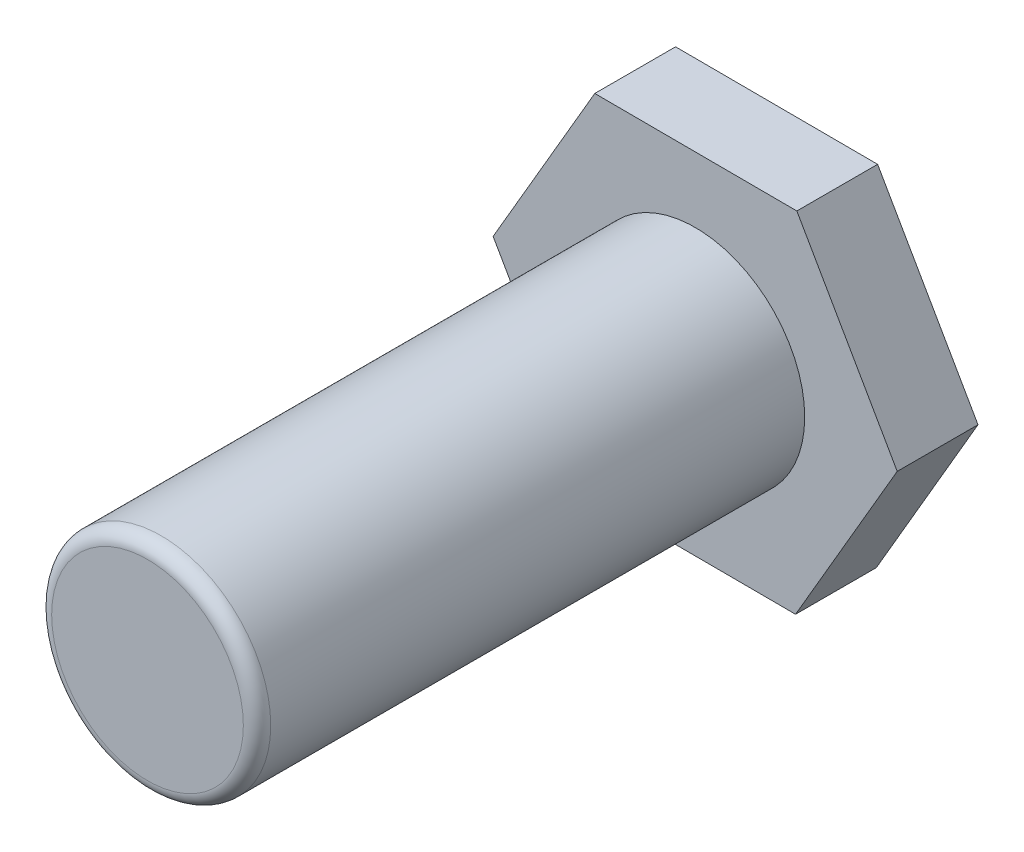
SolidWorks part; units mm, degrees
material "1.4021 (X20Cr13)"
ref_plane "Ön Düzlem" through (0, 0, 0) normal (0, 0, 1) x (1, 0, 0)
ref_plane "Üst Düzlem" through (0, 0, 0) normal (0, 1, 0) x (1, 0, 0)
ref_plane "Sağ Düzlem" through (0, 0, 0) normal (1, 0, 0) x (0, 0, -1)
sketch "Çizim2" plane through (0, 0, 0) normal (0, 0, 1) x (1, 0, 0)
  line L1 (3.7128, 6.3763) -> (-3.6656, 6.4036)
  line L2 (-3.6656, 6.4036) -> (-7.3785, 0.0273)
  line L3 (-7.3785, 0.0273) -> (-3.7128, -6.3763)
  line L4 (-3.7128, -6.3763) -> (3.6656, -6.4036)
  line L5 (3.6656, -6.4036) -> (7.3785, -0.0273)
  line L6 (7.3785, -0.0273) -> (3.7128, 6.3763)
  circle A0 centre (0, 0) radius 6.39 construction
  dimension "D1" = 12.78
extrude "Yükseklik-Ekstrüzyon1" add sketch "Çizim2" along normal blind 2.95
sketch "Çizim3" plane through (0, 0, 2.95) normal (0, 0, 1) x (1, 0, 0)
  circle A0 centre (0, 0) radius 4
  dimension "D1" = 8
extrude "Yükseklik-Ekstrüzyon2" add sketch "Çizim3" along normal blind 20
cosmetic thread "Kozmetik Diş Açma1" parameters "D2"=6.619
fillet "Radyus3" radius 0.5 1 edges at (4, 0, 22.95)
